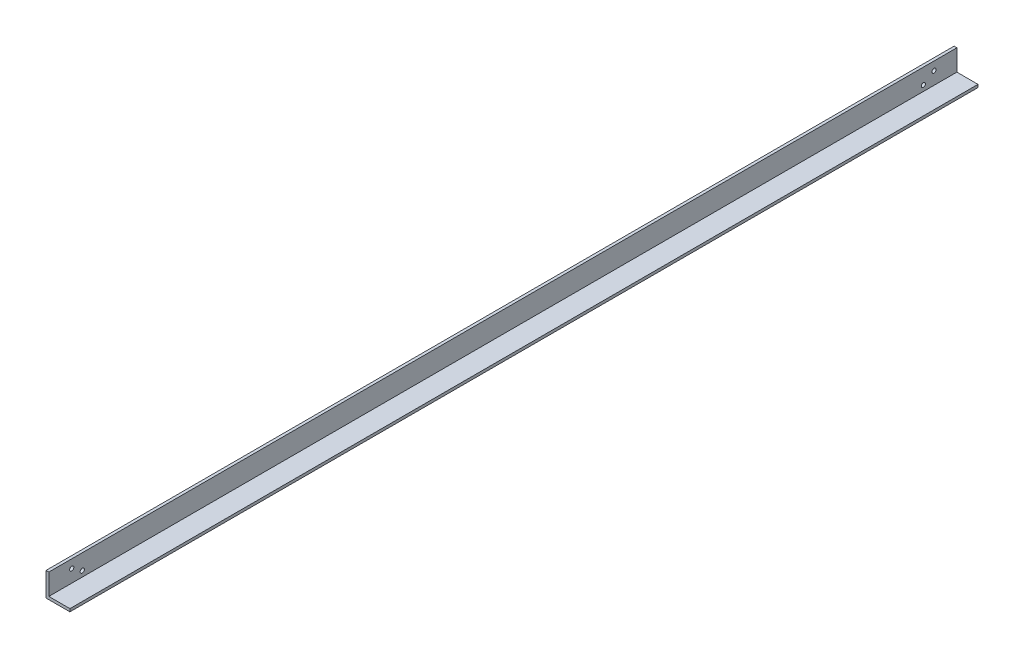
SolidWorks part; units mm, degrees
ref_plane "Спереди" through (0, 0, 0) normal (0, 0, 1) x (1, 0, 0)
ref_plane "Сверху" through (0, 0, 0) normal (0, 1, 0) x (1, 0, 0)
ref_plane "Справа" through (0, 0, 0) normal (1, 0, 0) x (0, 0, -1)
sketch "Эскиз1" plane through (0, 0, 0) normal (0, 0, 1) x (1, 0, 0)
  line L0 (0, 0) -> (0, 13)
  line L1 (0, 13) -> (-2, 13)
  line L2 (-2, 13) -> (-2, -2)
  line L3 (-2, -2) -> (13, -2)
  line L4 (13, -2) -> (13, 0)
  line L5 (13, 0) -> (0, 0)
  dimension "D1" = 2
  dimension "D2" = 2
  dimension "D3" = 15
  dimension "D4" = 15
extrude "Бобышка-Вытянуть1" add sketch "Эскиз1" against normal blind 645
sketch "Эскиз2" plane through (-2, 0, 0) normal (-1, 0, 0) x (0, 0, 1)
  line L0 (0, -2) -> (0, 4)
  line L1 (0, 13) -> (0, -2) construction
  line L2 (0, 4) -> (-23.79, 4)
  line L3 (0, 4) -> (-16.29, 4)
  line L4 (-16.29, 4) -> (-16.29, 9)
  line L5 (-322.5, 13) -> (-322.5, -2)
  line L6 (-645, 13) -> (0, 13) construction
  line L7 (-645, -2) -> (0, -2) construction
  line L8 (-628.71, 4) -> (-628.71, 9)
  line L9 (-645, 4) -> (-628.71, 4)
  line L10 (-645, 4) -> (-621.21, 4)
  line L11 (-645, -2) -> (-645, 4)
  circle A0 centre (-23.79, 4) radius 1.5
  circle A1 centre (-16.29, 9) radius 1.5
  circle A2 centre (-628.71, 9) radius 1.5
  circle A3 centre (-621.21, 4) radius 1.5
  dimension "D3" = 3
  dimension "D6" = 3
  dimension "D1" = 6
  dimension "D2" = 23.79
  dimension "D4" = 7.5
  dimension "D5" = 5
extrude "Вырез-Вытянуть2" cut sketch "Эскиз2" against normal through all
sketch "Эскиз3" plane through (0, 0, -645) normal (0, 0, -1) x (-1, 0, 0)
  line L1 (-13, -2) -> (-15, -2)
  line L2 (-13, -2) -> (-13, 0)
  line L3 (-13, 0) -> (-15, 0)
  line L4 (-15, -2) -> (-15, 0)
  line L5 (0, 13) -> (2, 13)
  line L6 (0, 13) -> (0, 15)
  line L7 (0, 15) -> (2, 15)
  line L8 (2, 13) -> (2, 15)
  dimension "D1" = 2
  dimension "D2" = 2
extrude "Бобышка-Вытянуть2" add sketch "Эскиз3" against normal up to surface (645 mm away) up to face at (3.6667, 3.6667, 0)
